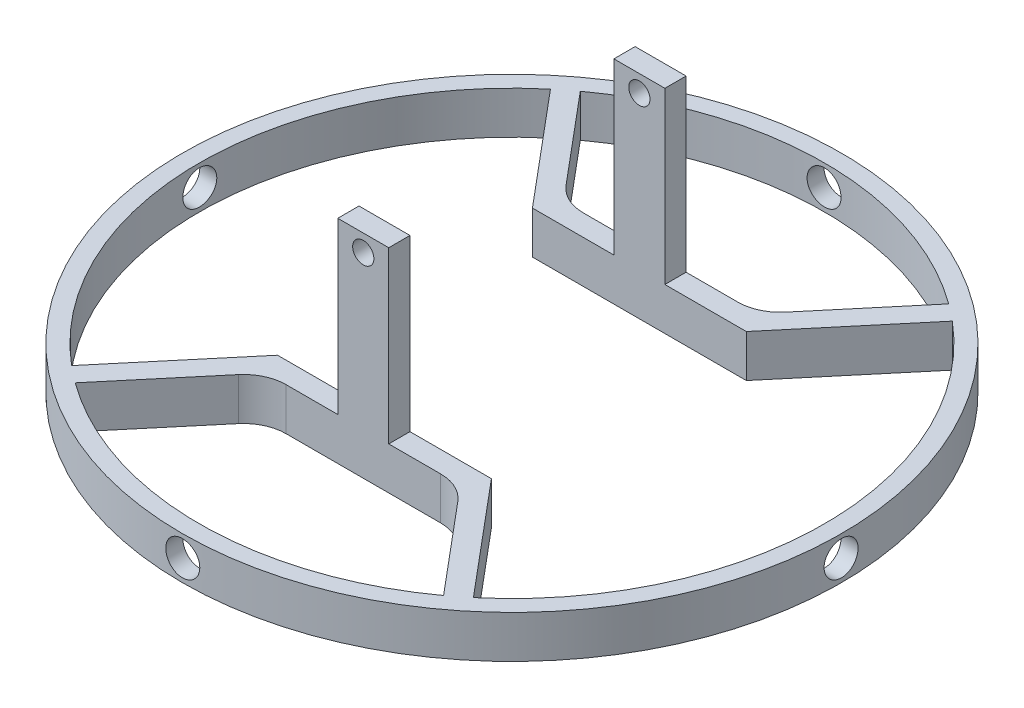
SolidWorks part; units mm, degrees
ref_plane "Alzado" through (0, 0, 0) normal (0, 0, 1) x (1, 0, 0)
ref_plane "Planta" through (0, 0, 0) normal (0, 1, 0) x (1, 0, 0)
ref_plane "Vista lateral" through (0, 0, 0) normal (1, 0, 0) x (0, 0, -1)
sketch "Croquis1" plane through (0, 0, 0) normal (0, 1, 0) x (1, 0, 0)
  line L1 (-15, -15) -> (15, -15)
  line L2 (-15, -15) -> (-15, 15)
  line L3 (-15, 15) -> (15, 15)
  line L4 (15, -15) -> (15, 15)
  line L5 (-15, -15) -> (15, 15) construction
  line L6 (-15, 15) -> (15, -15) construction
  circle A0 centre (0, 0) radius 11
  point P0 (0, 0)
  dimension "D3" = 22
  dimension "D4" = 4
  dimension "D1" = 30
  dimension "D2" = 30
sketch "Croquis2" plane through (0, 0, 0) normal (0, 1, 0) x (1, 0, 0)
  line L0 (-15, -15) -> (15, 15) construction
  line L2 (0, 15) -> (0, 0) construction
  line L4 (0, 0) -> (-36.79, 0) construction
  line L19 (12.5865, 15) -> (-12.5865, 15)
  line L20 (-12.5865, 15) -> (-23.6482, 28.1828)
  line L21 (12.5865, 15) -> (23.6482, 28.1828)
  line L22 (11.4207, 17.5) -> (21.733, 29.7897)
  line L23 (11.4207, 17.5) -> (-11.4207, 17.5)
  line L24 (-11.4207, 17.5) -> (-21.733, 29.7897)
  line L25 (12.5865, -15) -> (23.6482, -28.1828)
  line L26 (11.4207, -17.5) -> (21.733, -29.7897)
  line L27 (11.4207, -17.5) -> (-11.4207, -17.5)
  line L28 (-11.4207, -17.5) -> (-21.733, -29.7897)
  line L29 (-12.5865, -15) -> (-23.6482, -28.1828)
  line L30 (12.5865, -15) -> (-12.5865, -15)
  circle A0 centre (0, 0) radius 38.79
  circle A2 centre (0, 0) radius 36.79
  point P9 (0, 15)
  point P34 (0, 0)
  dimension "D1" = 77.58
  dimension "D3" = 15
  dimension "D4" = 2.5
  dimension "D5" = 130
  dimension "D6" = 130
  dimension "D2" = 2
extrude "Saliente-Extruir1" add sketch "Croquis2" along normal blind 5
ref_plane "Plano1" through (0, 0, 15) normal (0, 0, 1) x (1, 0, 0)
sketch "Croquis3" plane through (0, 0, 0) normal (0, 1, 0) x (1, 0, 0)
  line L1 (-15, -15) -> (15, -15)
  line L2 (-15, -15) -> (-15, 15)
  line L3 (-15, 15) -> (15, 15)
  line L4 (15, -15) -> (15, 15)
  line L5 (-15, -15) -> (15, 15) construction
  line L6 (-15, 15) -> (15, -15) construction
  line L7 (-12.5, -12.5) -> (-12.5, 12.5)
  line L8 (-12.5, 12.5) -> (12.5, 12.5)
  line L9 (12.5, -12.5) -> (12.5, 12.5)
  line L10 (-12.5, -12.5) -> (12.5, -12.5)
  dimension "D1" = 2.5
  dimension "D2" = 30
sketch "Croquis4" plane through (0, 0, 15) normal (0, 0, 1) x (1, 0, 0)
  line L0 (-15, 0) -> (15, 0) construction
  line L1 (-3, 25) -> (3, 25)
  line L2 (-3, 25) -> (-3, 0)
  line L3 (-3, 0) -> (3, 0)
  line L4 (3, 25) -> (3, 0)
  line L5 (-3, 25) -> (3, 0) construction
  line L6 (-3, 0) -> (3, 25) construction
  point P0 (0, 12.5)
  dimension "D1" = 25
  dimension "D2" = 6
  dimension "D3" = 3
extrude "Saliente-Extruir3" add sketch "Croquis4" along normal blind 2.5
mirror "Simetría1" about plane through (0, 0, 0) normal (0, 0, 1) of "Saliente-Extruir3"
sketch "Croquis5" plane through (0, 0, -17.5) normal (0, 0, -1) x (-1, 0, 0)
  line L0 (0, 25) -> (0, 23) construction
  line L1 (-3, 25) -> (3, 25) construction
  line L2 (0, 23) -> (3, 23) construction
  line L3 (3, 25) -> (3, 5) construction
  circle A0 centre (0, 23) radius 1.25
  dimension "D1" = 2
  dimension "D2" = 2.5
extrude "Cortar-Extruir1" cut sketch "Croquis5" against normal through all both and the other way through all
fillet "Redondeo1" radius 5 4 edges at (11.4207, 2.5, -17.5) (-11.4207, 2.5, -17.5) (11.4207, 2.5, 17.5) (-11.4207, 2.5, 17.5)
sketch "Croquis6" plane through (0, 0, 0) normal (0, 0, 1) x (1, 0, 0)
  line L0 (0, 0) -> (0, 5) construction
  line L2 (38.79, 5) -> (-38.79, 5) construction
  circle A0 centre (0, 2.5) radius 2
  point P3 (0, 5)
  point P7 (0, 0)
  dimension "D1" = 4
extrude "Cortar-Extruir2" cut sketch "Croquis6" against normal blind 17 from offset 50
pattern_circular "MatrizC1" count 4 over 360 of "Cortar-Extruir2"
